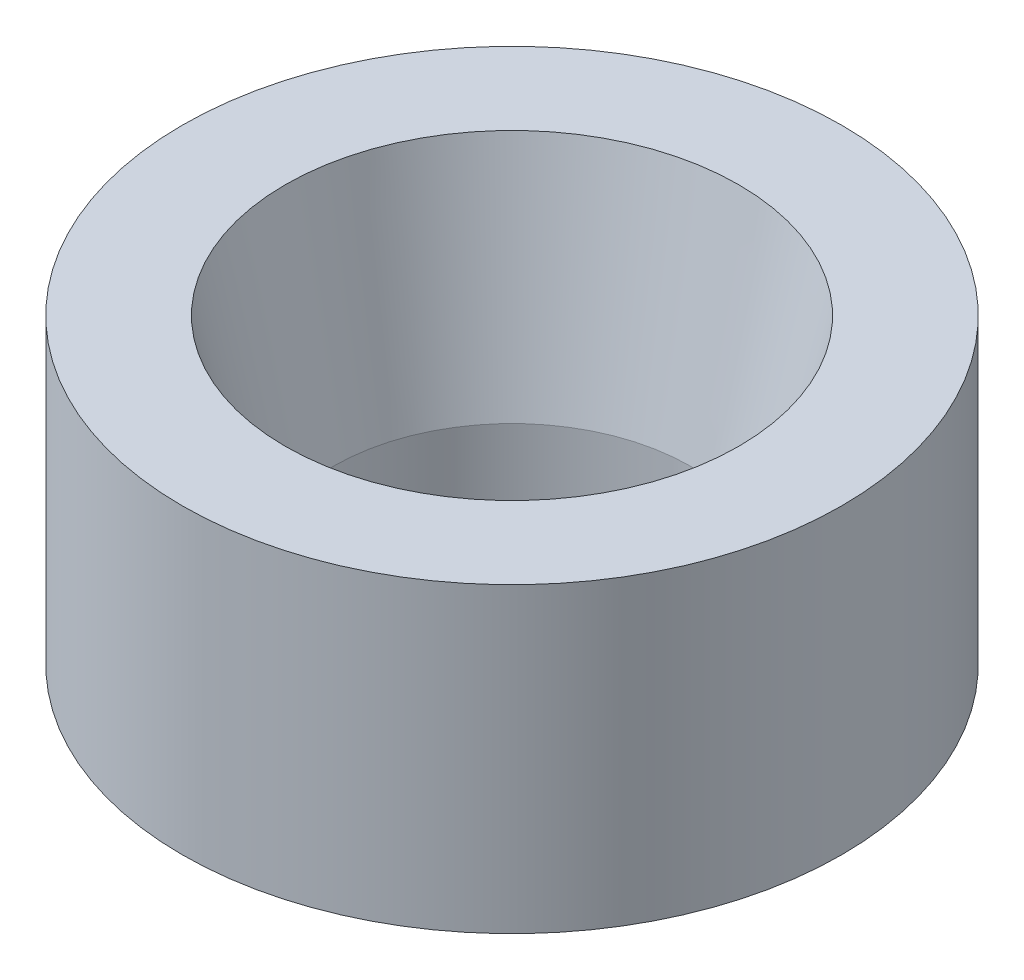
SolidWorks part; units mm, degrees
material "AISI 1045 Steel, cold drawn"
ref_plane "Front Plane" through (0, 0, 0) normal (0, 0, 1) x (1, 0, 0)
ref_plane "Top Plane" through (0, 0, 0) normal (0, 1, 0) x (1, 0, 0)
ref_plane "Right Plane" through (0, 0, 0) normal (1, 0, 0) x (0, 0, -1)
sketch "Sketch1" plane through (0, 0, 0) normal (0, 0, 1) x (1, 0, 0)
  line L0 (13, 0) -> (13, 6)
  line L1 (13, 6) -> (16.5, 22)
  line L2 (16.5, 22) -> (24, 22)
  line L3 (24, 22) -> (24, 0)
  line L4 (24, 0) -> (13, 0)
  line L5 (0, 34.5537) -> (0, -9.9435) construction
  dimension "D1" = 22
  dimension "D2" = 6
  dimension "D3" = 7.5
  dimension "D4" = 24
  dimension "D5" = 13
revolve "Revolve1" add sketch "Sketch1" angle 360 about L5
